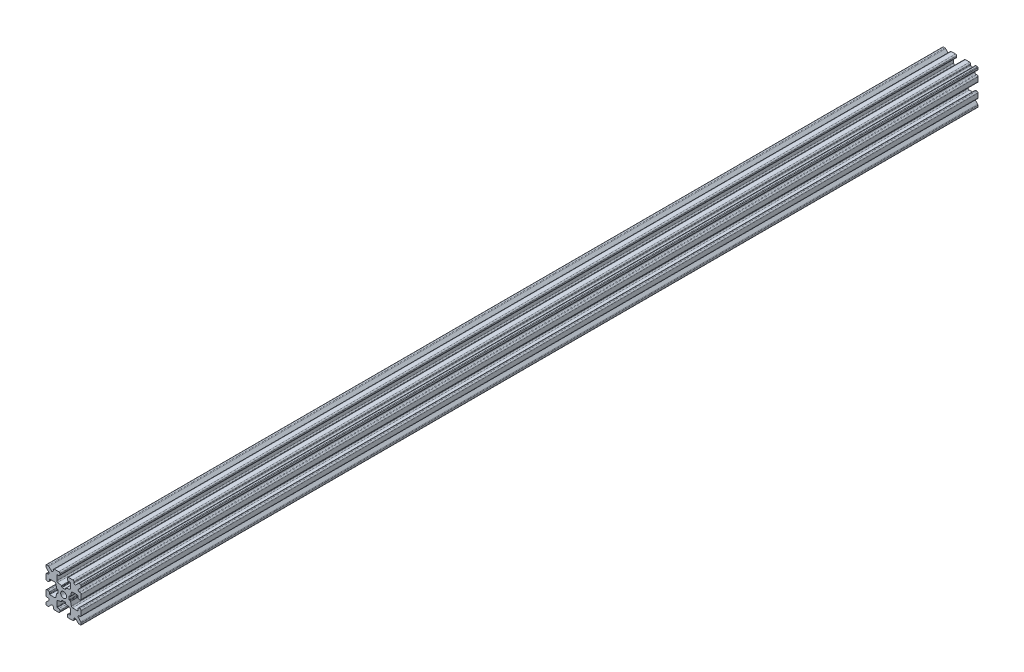
SolidWorks part; units mm, degrees
material "1060 Alloy"
ref_plane "Front Plane" through (0, 0, 0) normal (0, 0, 1) x (1, 0, 0)
ref_plane "Top Plane" through (0, 0, 0) normal (0, 1, 0) x (1, 0, 0)
ref_plane "Right Plane" through (0, 0, 0) normal (1, 0, 0) x (0, 0, -1)
sketch "Sketch1" plane through (0, 0, 0) normal (0, 0, 1) x (1, 0, 0)
  line L1 (-7.5, -7.5) -> (7.5, -7.5)
  line L2 (-7.5, -7.5) -> (-7.5, 7.5)
  line L3 (-7.5, 7.5) -> (7.5, 7.5)
  line L4 (7.5, -7.5) -> (7.5, 7.5)
  line L5 (-7.5, -7.5) -> (7.5, 7.5) construction
  line L6 (-7.5, 7.5) -> (7.5, -7.5) construction
  circle A0 centre (0, 0) radius 1.25
  point P0 (0, 0)
  dimension "D2" = 2.5
  dimension "D1" = 15
extrude "Boss-Extrude1" add sketch "Sketch1" along normal mid plane 382
fillet "Fillet1" radius 0.25 4 edges at (7.5, -7.5, 0) (-7.5, -7.5, 0) (7.5, 7.5, 0) (-7.5, 7.5, 0)
sketch "Sketch2" plane through (0, 0, 191) normal (0, 0, 1) x (1, 0, 0)
  line L0 (-7.5, 7.25) -> (-7.5, -7.25) construction
  line L1 (-7.5, 1.6) -> (-6.1, 1.6)
  line L2 (-7.5, 1.6) -> (-7.5, -1.6)
  line L3 (-7.5, -1.6) -> (-6.1, -1.6)
  line L4 (-6.1, 1.6) -> (-6.1, 2.9)
  line L5 (0, 0) -> (-12.1036, 0) construction
  line L6 (-6.1, -2.9) -> (-3.4, -2.9)
  line L7 (0, 0) -> (-7.25, 7.25) construction
  line L8 (-6.1, 2.9) -> (-3.4, 2.9)
  line L9 (-3.4, -2.9) -> (-3.4, 2.9)
  line L10 (55, 0) -> (-55, 0) construction
  line L11 (-6.1, -2.9) -> (-6.1, -1.6)
  line L12 (2.9, 6.1) -> (1.6, 6.1)
  line L13 (2.9, 3.4) -> (-2.9, 3.4)
  line L14 (-2.9, 6.1) -> (-2.9, 3.4)
  line L15 (2.9, 6.1) -> (2.9, 3.4)
  line L16 (-1.6, 6.1) -> (-2.9, 6.1)
  line L17 (1.6, 7.5) -> (1.6, 6.1)
  line L18 (-1.6, 7.5) -> (1.6, 7.5)
  line L19 (-1.6, 7.5) -> (-1.6, 6.1)
  line L20 (-1.6, -7.5) -> (-1.6, -6.1)
  line L21 (-1.6, -7.5) -> (1.6, -7.5)
  line L22 (1.6, -7.5) -> (1.6, -6.1)
  line L23 (-1.6, -6.1) -> (-2.9, -6.1)
  line L24 (2.9, -6.1) -> (2.9, -3.4)
  line L25 (-2.9, -6.1) -> (-2.9, -3.4)
  line L26 (2.9, -3.4) -> (-2.9, -3.4)
  line L27 (2.9, -6.1) -> (1.6, -6.1)
  line L28 (6.1, -2.9) -> (6.1, -1.6)
  line L29 (3.4, -2.9) -> (3.4, 2.9)
  line L30 (6.1, 2.9) -> (3.4, 2.9)
  line L31 (6.1, -2.9) -> (3.4, -2.9)
  line L32 (6.1, 1.6) -> (6.1, 2.9)
  line L33 (7.5, -1.6) -> (6.1, -1.6)
  line L34 (7.5, 1.6) -> (7.5, -1.6)
  line L35 (7.5, 1.6) -> (6.1, 1.6)
  dimension "D1" = 3.2
  dimension "D2" = 5.8
  dimension "D3" = 1.4
  dimension "D4" = 2.7
extrude "Cut-Extrude1" cut sketch "Sketch2" against normal through all
sketch "Sketch4" plane through (0, 0, 191) normal (0, 0, 1) x (1, 0, 0)
  line L0 (-3.4, 2.9) -> (-2.75, 0)
  line L1 (55, 0) -> (-55, 0) construction
  line L2 (-2.75, 0) -> (-3.4, -2.9)
  line L3 (-3.4, -2.9) -> (-3.4, 2.9) construction
  line L4 (-3.4, 2.9) -> (-3.4, -2.9)
  line L5 (-2.9, 3.4) -> (0, 2.75)
  line L6 (0, 2.75) -> (2.9, 3.4)
  line L7 (2.9, 3.4) -> (-2.9, 3.4)
  line L8 (3.4, 2.9) -> (2.75, 0)
  line L9 (2.75, 0) -> (3.4, -2.9)
  line L10 (3.4, -2.9) -> (3.4, 2.9)
  line L11 (-2.9, -3.4) -> (0, -2.75)
  line L12 (0, -2.75) -> (2.9, -3.4)
  line L13 (2.9, -3.4) -> (-2.9, -3.4)
  circle A2 centre (0, 0) radius 2.75
  circle A3 centre (0, 0) radius 2.75 construction
  dimension "D1" = 1.5
extrude "Cut-Extrude3" cut sketch "Sketch4" against normal through all
fillet "Fillet3" radius 0.5 16 edges at (-6.1, -1.6, 0) (-7.5, -1.6, 0) (-6.1, 1.6, 0) (-7.5, 1.6, 0) (-1.6, -7.5, 0) (-1.6, -6.1, 0) (1.6, -7.5, 0) (1.6, -6.1, 0) (6.1, -1.6, 0) (7.5, -1.6, 0) (7.5, 1.6, 0) (6.1, 1.6, 0) (1.6, 7.5, 0) (1.6, 6.1, 0) (-1.6, 7.5, 0) (-1.6, 6.1, 0)
fillet "Fillet4" radius 0.5 8 edges at (-3.4, 2.9, 0) (-3.4, -2.9, 0) (2.9, -3.4, 0) (-2.9, -3.4, 0) (3.4, -2.9, 0) (3.4, 2.9, 0) (-2.9, 3.4, 0) (2.9, 3.4, 0)
fillet "Fillet5" radius 3 4 edges at (0, -2.75, 0) (2.75, 0, 0) (-2.75, 0, 0) (0, 2.75, 0)
fillet "Fillet6" radius 0.2 8 edges at (-2.9, -6.1, 0) (2.9, -6.1, 0) (6.1, -2.9, 0) (6.1, 2.9, 0) (2.9, 6.1, 0) (-2.9, 6.1, 0) (-6.1, -2.9, 0) (-6.1, 2.9, 0)
sketch "Sketch5" plane through (0, 0, 191) normal (0, 0, 1) x (1, 0, 0)
  line L0 (0, 0) -> (-7.25, 7.25) construction
  line L1 (-7.5, 6.4393) -> (-5.4607, 4.4)
  line L2 (-6.4393, 7.5) -> (-4.4, 5.4607)
  line L3 (-7.5, 4.4) -> (-5.4607, 4.4)
  line L4 (-3.8003, 2.9) -> (-5.9, 2.9) construction
  line L5 (0, 0) -> (-12.1819, 0) construction
  line L6 (-4.4, 7.5) -> (-4.4, 5.4607)
  line L7 (-2.9, 5.9) -> (-2.9, 3.8003) construction
  line L8 (-7.5, 6.4393) -> (-7.5, 4.4)
  line L9 (-7.5, 7.25) -> (-7.5, 2.1) construction
  line L10 (2.1, -7.5) -> (7.25, -7.5) construction
  line L11 (7.5, -7.25) -> (7.5, -2.1) construction
  line L12 (7.25, 7.5) -> (2.1, 7.5) construction
  line L13 (-2.1, 7.5) -> (-7.25, 7.5) construction
  line L14 (-4.4, 7.5) -> (-6.4393, 7.5)
  line L16 (55, 0) -> (-55, 0) construction
  line L17 (0, 0) -> (0, 10.993) construction
  line L18 (0, -54.6431) -> (0, 54.6431) construction
  line L20 (4.4, 7.5) -> (6.4393, 7.5)
  line L22 (7.5, 6.4393) -> (7.5, 4.4)
  line L23 (4.4, 7.5) -> (4.4, 5.4607)
  line L24 (7.5, 4.4) -> (5.4607, 4.4)
  line L25 (6.4393, 7.5) -> (4.4, 5.4607)
  line L26 (7.5, 6.4393) -> (5.4607, 4.4)
  line L27 (7.5, -6.4393) -> (5.4607, -4.4)
  line L28 (6.4393, -7.5) -> (4.4, -5.4607)
  line L29 (7.5, -4.4) -> (5.4607, -4.4)
  line L30 (4.4, -7.5) -> (4.4, -5.4607)
  line L31 (7.5, -6.4393) -> (7.5, -4.4)
  line L33 (4.4, -7.5) -> (6.4393, -7.5)
  line L36 (-4.4, -7.5) -> (-6.4393, -7.5)
  line L38 (-7.5, -6.4393) -> (-7.5, -4.4)
  line L39 (-4.4, -7.5) -> (-4.4, -5.4607)
  line L40 (-7.5, -4.4) -> (-5.4607, -4.4)
  line L41 (-6.4393, -7.5) -> (-4.4, -5.4607)
  line L42 (-7.5, -6.4393) -> (-5.4607, -4.4)
  dimension "D1" = 1.5
  dimension "D2" = 1.5
  dimension "D3" = 1.5
extrude "Cut-Extrude4" cut sketch "Sketch5" against normal through all
fillet "Fillet8" radius 0.5 24 edges at (-5.4607, 4.4, 0) (-7.5, 4.4, 0) (-5.4607, -4.4, 0) (-7.5, -4.4, 0) (-4.4, -7.5, 0) (-4.4, -5.4607, 0) (4.4, -7.5, 0) (4.4, -5.4607, 0) (5.4607, -4.4, 0) (7.5, -4.4, 0) (7.5, 4.4, 0) (5.4607, 4.4, 0) (4.4, 5.4607, 0) (4.4, 7.5, 0) (-4.4, 5.4607, 0) (-4.4, 7.5, 0) (-6.4393, 7.5, 0) (-7.5, 6.4393, 0) (6.4393, 7.5, 0) (7.5, 6.4393, 0) (6.4393, -7.5, 0) (7.5, -6.4393, 0) (-6.4393, -7.5, 0) (-7.5, -6.4393, 0)
sketch "Sketch6" plane through (0, 0, 191) normal (0, 0, 1) x (1, 0, 0)
  line L0 (0, 0) -> (0, 11.013) construction
  line L1 (0.6561, 2.8971) -> (2.1235, 2.8971) construction
  line L2 (0, -54.6431) -> (0, 54.6431) construction
  line L3 (0, 0) -> (7.25, 7.25) construction
  line L4 (7.5, 0.8255) -> (7.5, -0.8255)
  line L5 (2.3471, 0.8255) -> (7.5, 0.8255)
  line L6 (0, 0) -> (12.4016, 0) construction
  line L7 (0.8255, -7.5) -> (-0.8255, -7.5)
  line L8 (2.3471, -0.8255) -> (2.3471, 0.8255)
  line L9 (0.8255, -2.3471) -> (0.8255, -7.5)
  line L10 (7.5, -0.8255) -> (2.3471, -0.8255)
  line L11 (-7.5, -0.8255) -> (-2.3471, -0.8255)
  line L12 (-2.3471, -0.8255) -> (-2.3471, 0.8255)
  line L13 (-0.8255, -2.3471) -> (0.8255, -2.3471)
  line L14 (-0.8255, 7.5) -> (-0.8255, 2.3471)
  line L15 (-0.8255, 2.3471) -> (0.8255, 2.3471)
  line L16 (-0.8255, -7.5) -> (-0.8255, -2.3471)
  line L17 (0.8255, 2.3471) -> (0.8255, 7.5)
  line L18 (0.8255, 7.5) -> (-0.8255, 7.5)
  line L19 (3.9, 7.5) -> (2.1, 7.5) construction
  line L20 (-2.3471, 0.8255) -> (-7.5, 0.8255)
  line L21 (-7.5, 0.8255) -> (-7.5, -0.8255)
  point P5 (0, -2.5973)
  point P7 (0, 2.5973)
  dimension "D3" = 0.55
  dimension "D1" = 1.651
extrude "Cut-Extrude5" cut sketch "Sketch6" against normal through all
fillet "Fillet10" radius 0.2 16 edges at (-2.935, 0.8255, 0) (-2.935, -0.8255, 0) (2.935, -0.8255, 0) (2.935, 0.8255, 0) (0.8255, 2.935, 0) (-0.8255, 2.935, 0) (-2.3471, 0.8255, 0) (-2.3471, -0.8255, 0) (0.8255, 2.3471, 0) (-0.8255, 2.3471, 0) (2.3471, 0.8255, 0) (2.3471, -0.8255, 0) (0.8255, -2.935, 0) (0.8255, -2.3471, 0) (-0.8255, -2.3471, 0) (-0.8255, -2.935, 0)
